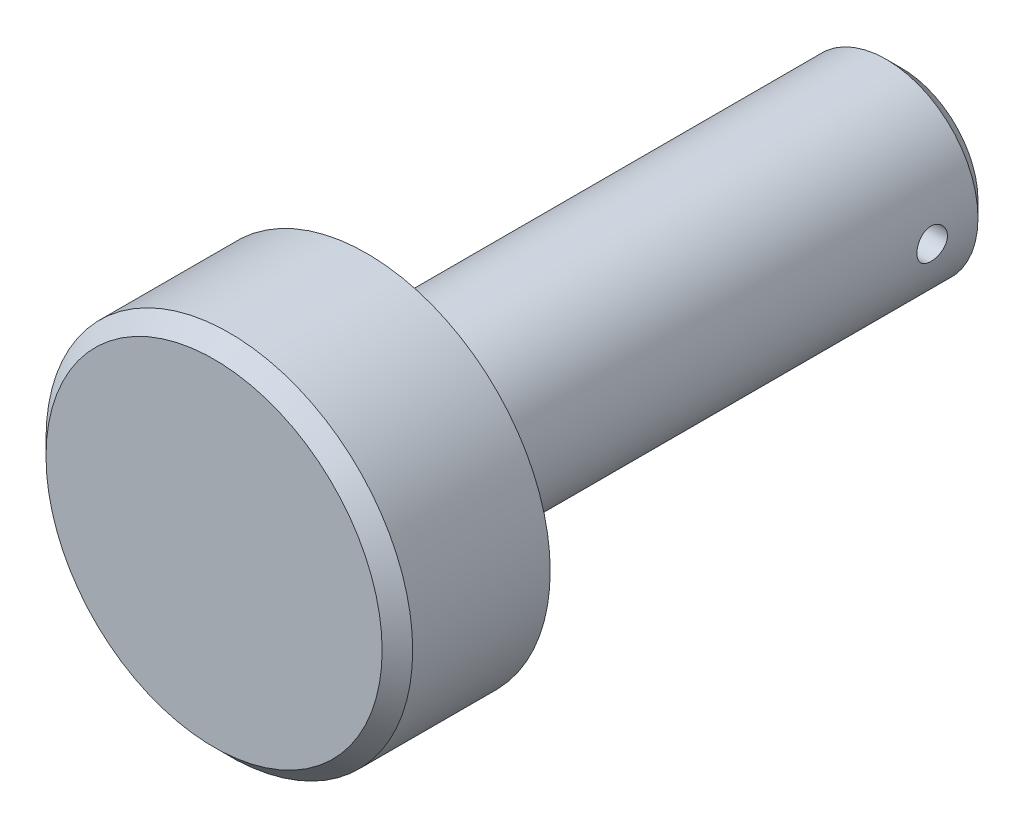
SolidWorks part; units mm, degrees
ref_plane "前基準面" through (0, 0, 0) normal (0, 0, 1) x (1, 0, 0)
ref_plane "上基準面" through (0, 0, 0) normal (0, 1, 0) x (1, 0, 0)
ref_plane "右基準面" through (0, 0, 0) normal (1, 0, 0) x (0, 0, -1)
sketch "草圖1" plane through (0, 0, 0) normal (1, 0, 0) x (0, 0, -1)
  line L0 (0, 0) -> (72.7659, 0) construction
  line L1 (0, 0) -> (0, 12)
  line L2 (0, 12) -> (10, 12)
  line L3 (10, 12) -> (10, 6)
  line L4 (10, 6) -> (45, 6)
  line L5 (45, 6) -> (45, 0)
  line L6 (0, 0) -> (45, 0)
  dimension "D1" = 12
  dimension "D2" = 24
  dimension "D3" = 10
  dimension "D4" = 45
revolve "旋轉1" add sketch "草圖1" angle 360 about L0
chamfer "導角1" distance 1 angle 45 2 edges at (6, 0, -45) (12, 0, 0)
sketch "草圖2" plane through (0, 0, 0) normal (1, 0, 0) x (0, 0, -1)
  line L0 (45, -5) -> (45, 5) construction
  circle A0 centre (41, 0) radius 1
  dimension "D1" = 2
  dimension "D2" = 4
extrude "伸長1" cut sketch "草圖2" against normal through all and the other way through all
